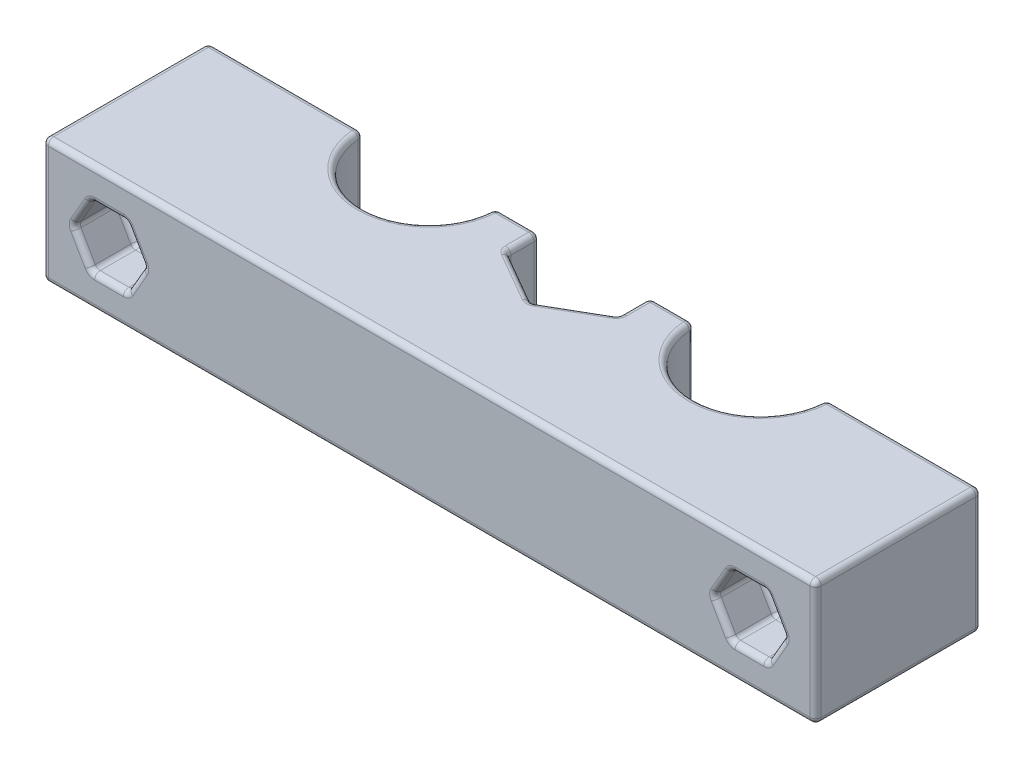
SolidWorks part; units mm, degrees
ref_plane "Front Plane" through (0, 0, 0) normal (0, 0, 1) x (1, 0, 0)
ref_plane "Top Plane" through (0, 0, 0) normal (0, 1, 0) x (1, 0, 0)
ref_plane "Right Plane" through (0, 0, 0) normal (1, 0, 0) x (0, 0, -1)
sketch "Sketch1" plane through (0, 0, 0) normal (0, 1, 0) x (1, 0, 0)
  line L0 (35, 0) -> (35, 15) construction
  line L1 (0, 0) -> (70, 0) construction
  line L2 (0, 0) -> (0, 15) construction
  line L3 (0, 15) -> (70, 15) construction
  line L4 (70, 0) -> (70, 15) construction
  line L5 (35, 9.2265) -> (40, 12.1132) construction
  line L6 (40, 12.1132) -> (40, 17.8868) construction
  line L7 (40, 17.8868) -> (35, 20.7735) construction
  line L8 (35, 20.7735) -> (30, 17.8868) construction
  line L9 (30, 17.8868) -> (30, 12.1132) construction
  line L10 (30, 12.1132) -> (35, 9.2265) construction
  line L11 (56, 15) -> (70, 15)
  line L12 (70, 15) -> (70, 0)
  line L13 (70, 0) -> (0, 0)
  line L14 (0, 0) -> (0, 15)
  line L15 (0, 15) -> (14, 15)
  line L16 (26, 15) -> (30, 15)
  line L21 (40, 15) -> (44, 15)
  line L22 (30, 15) -> (30, 12.1132)
  line L23 (30, 12.1132) -> (35, 9.2265)
  line L24 (35, 9.2265) -> (40, 12.1132)
  line L25 (40, 12.1132) -> (40, 15)
  circle A0 centre (35, 15) radius 5 construction
  circle A1 centre (20, 15) radius 6 construction
  circle A2 centre (50, 15) radius 6 construction
  arc A3 (14, 15) -> (26, 15) centre (20, 15) ccw
  arc A4 (44, 15) -> (56, 15) centre (50, 15) ccw
  dimension "D4" = 12
  dimension "D1" = 15
  dimension "D2" = 10
  dimension "D3" = 70
  dimension "D5" = 15
extrude "Boss-Extrude1" add sketch "Sketch1" along normal blind 11.3
sketch "Sketch2" plane through (0, 0, 0) normal (0, 0, 1) x (1, 0, 0)
  line L0 (35, 11.3) -> (35, 0) construction
  line L1 (0, 0) -> (70, 0) construction
  line L2 (0, 5.65) -> (6, 5.65) construction
  line L3 (0, 11.3) -> (0, 0) construction
  circle A0 centre (6, 5.65) radius 1.6
  circle A1 centre (64, 5.65) radius 1.6
  dimension "D2" = 3.2
  dimension "D1" = 6
extrude "Cut-Extrude1" cut sketch "Sketch2" against normal through all
sketch "Sketch4" plane through (0, 0, 0) normal (0, 0, 1) x (1, 0, 0)
  line L0 (35, 11.3) -> (35, 0) construction
  line L1 (9.1754, 5.65) -> (7.5877, 8.4)
  line L2 (7.5877, 8.4) -> (4.4123, 8.4)
  line L3 (4.4123, 8.4) -> (2.8246, 5.65)
  line L4 (2.8246, 5.65) -> (4.4123, 2.9)
  line L5 (4.4123, 2.9) -> (7.5877, 2.9)
  line L6 (7.5877, 2.9) -> (9.1754, 5.65)
  line L7 (0, 11.3) -> (70, 11.3) construction
  line L8 (62.4123, 2.9) -> (60.8246, 5.65)
  line L9 (65.5877, 2.9) -> (62.4123, 2.9)
  line L10 (67.1754, 5.65) -> (65.5877, 2.9)
  line L11 (65.5877, 8.4) -> (67.1754, 5.65)
  line L12 (62.4123, 8.4) -> (65.5877, 8.4)
  line L13 (60.8246, 5.65) -> (62.4123, 8.4)
  circle A0 centre (6, 5.65) radius 2.75 construction
  circle A1 centre (6, 5.65) radius 1.6 construction
  dimension "D1" = 5.5
extrude "Cut-Extrude3" cut sketch "Sketch4" against normal blind 4.2
fillet "Fillet5" radius 0.5 79 edges at (62.4123, 8.4, -2.1) (60.8246, 5.65, -2.1) (62.4123, 2.9, -2.1) (65.5877, 2.9, -2.1) (67.1754, 5.65, -2.1) (65.5877, 8.4, -2.1) (62.4, 5.65, -4.2) (61.6184, 4.275, -4.2) (61.6184, 7.025, -4.2) (64, 8.4, -4.2) (66.3816, 7.025, -4.2) (66.3816, 4.275, -4.2) (64, 2.9, -4.2) (7.5877, 2.9, -2.1) (9.1754, 5.65, -2.1) (2.8246, 5.65, -2.1) (4.4123, 2.9, -2.1) (7.5877, 8.4, -2.1) (4.4123, 8.4, -2.1) (7.6, 5.65, -4.2) (6, 2.9, -4.2) (3.6184, 4.275, -4.2) (3.6184, 7.025, -4.2) (6, 8.4, -4.2) (8.3816, 7.025, -4.2) (8.3816, 4.275, -4.2) (70, 0, -7.5) (40, 0, -13.5566) (30, 0, -13.5566) (0, 0, -7.5) (70, 5.65, -15) (63, 0, -15) (62.4, 5.65, -15) (56, 5.65, -15) (50, 0, -9) (44, 5.65, -15) (40, 5.65, -15) (42, 0, -15) (40, 5.65, -12.1132) (37.5, 0, -10.6699) (35, 5.65, -9.2265) (30, 5.65, -12.1132) (32.5, 0, -10.6699) (30, 5.65, -15) (28, 0, -15) (26, 5.65, -15) (20, 0, -9) (14, 5.65, -15) (0, 5.65, -15) (7, 0, -15) (7.6, 5.65, -15) (7, 11.3, -15) (20, 11.3, -9) (28, 11.3, -15) (30, 11.3, -13.5566) (32.5, 11.3, -10.6699) (37.5, 11.3, -10.6699) (40, 11.3, -13.5566) (42, 11.3, -15) (50, 11.3, -9) (63, 11.3, -15) (70, 11.3, -7.5) (0, 11.3, -7.5) (0, 5.65, 0) (35, 11.3, 0) (70, 5.65, 0) (35, 0, 0) (66.3816, 7.025, 0) (64, 8.4, 0) (61.6184, 7.025, 0) (61.6184, 4.275, 0) (64, 2.9, 0) (66.3816, 4.275, 0) (6, 8.4, 0) (3.6184, 7.025, 0) (3.6184, 4.275, 0) (6, 2.9, 0) (8.3816, 4.275, 0) (8.3816, 7.025, 0)
